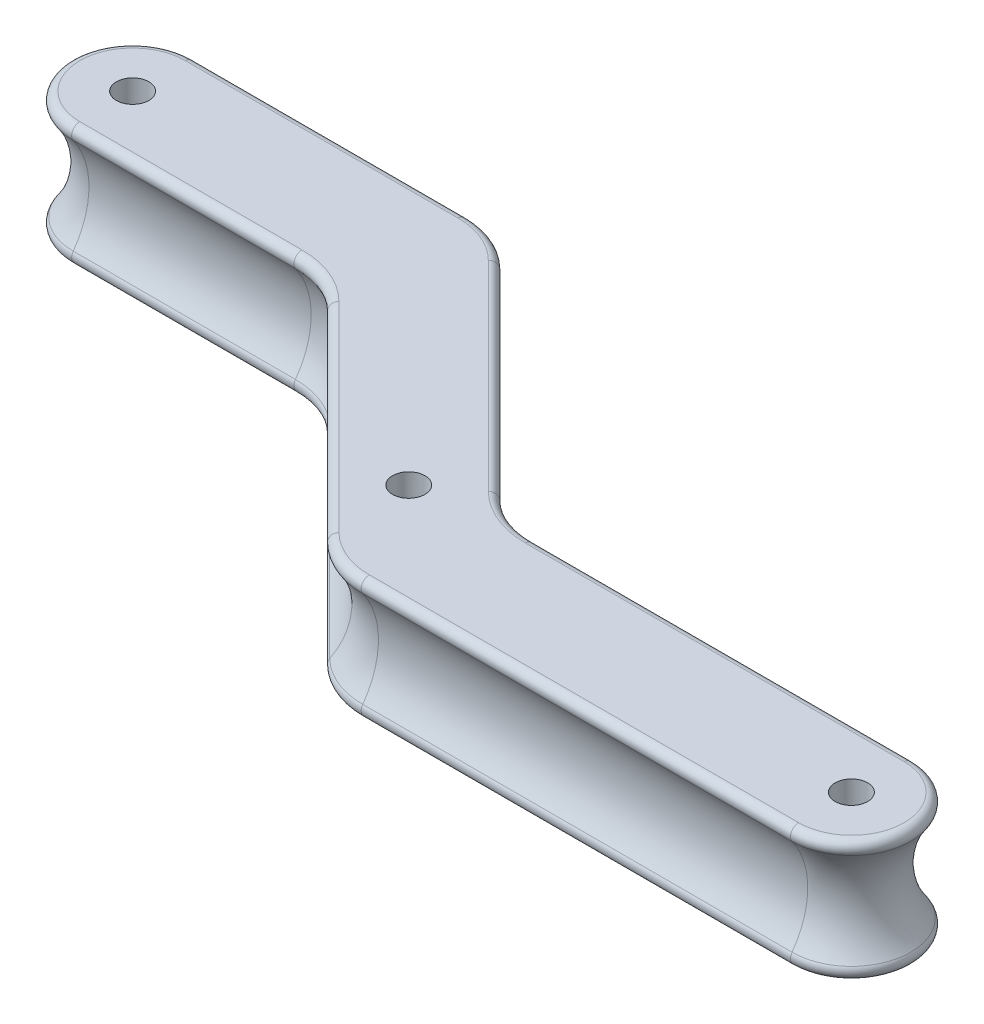
SolidWorks part; units mm, degrees
material "ABS"
ref_plane "前视基准面" through (0, 0, 0) normal (0, 0, 1) x (1, 0, 0)
ref_plane "上视基准面" through (0, 0, 0) normal (0, 1, 0) x (1, 0, 0)
ref_plane "右视基准面" through (0, 0, 0) normal (1, 0, 0) x (0, 0, -1)
sketch "草图1" plane through (0, 0, 0) normal (0, 1, 0) x (1, 0, 0)
  line L12 (-181.5, 30.5) -> (-150, 30.5)
  line L28 (-181.5, 45.5) -> (-143.7868, 45.5)
  line L31 (-150, 30.5) -> (-119.5, 0)
  line L39 (0, 0) -> (0, 70) construction
  line L61 (-113.2868, 15) -> (-62.5, 15)
  line L64 (-113.2868, 15) -> (-143.7868, 45.5)
  line L80 (-119.5, 0) -> (-62.5, 0)
  arc A9 (-181.5, 45.5) -> (-181.5, 30.5) centre (-181.5, 38) ccw
  arc A10 (-62.5, 0) -> (-62.5, 15) centre (-62.5, 7.5) ccw
  dimension "D3" = 119
  dimension "D5" = 15
  dimension "D6" = 15
  dimension "D9" = 45.5
  dimension "D8" = 150
  dimension "D2" = 62.5
  dimension "D18" = 135
  dimension "D19" = 15
extrude "凸台-拉伸1" add sketch "草图1" along normal mid plane 15
sketch "草图2" plane through (0, 7.5, 0) normal (0, 1, 0) x (1, 0, 0)
  line L0 (-143.7868, 45.5) -> (-181.5, 45.5) construction
  circle A0 centre (-62.5, 7.5) radius 2
  circle A41 centre (-181.5, 38) radius 2
  circle A42 centre (-122.5, 13) radius 2
  dimension "D2" = 32.5
  dimension "D3" = 59
  dimension "D19" = 4
extrude "切除-拉伸1" cut sketch "草图2" against normal through all
fillet "圆角1" radius 10 4 edges at (-150, 0, -30.5) (-143.7868, 0, -45.5) (-119.5, 0, 0) (-113.2868, 0, -15)
sketch "草图4" plane through (0, 7.5, 0) normal (0, 1, 0) x (1, 0, 0)
  line L16 (-62.5, 15) -> (-109.1447, 15)
  line L17 (-116.2157, 17.9289) -> (-140.8579, 42.5711)
  line L18 (-147.9289, 45.5) -> (-181.5, 45.5)
  line L23 (-181.5, 30.5) -> (-154.1421, 30.5)
  line L24 (-147.0711, 27.5711) -> (-122.4289, 2.9289)
  line L25 (-115.3579, 0) -> (-62.5, 0)
  line L29 (-62.5, 15) -> (-109.1447, 15)
  line L30 (-116.2157, 17.9289) -> (-140.8579, 42.5711)
  line L31 (-147.9289, 45.5) -> (-181.5, 45.5)
  line L36 (-181.5, 30.5) -> (-154.1421, 30.5)
  line L37 (-147.0711, 27.5711) -> (-122.4289, 2.9289)
  line L38 (-115.3579, 0) -> (-62.5, 0)
  arc A6 (-62.5, 0) -> (-62.5, 15) centre (-62.5, 7.5) ccw
  arc A7 (-62.5, 0) -> (-62.5, 15) centre (-62.5, 7.5) ccw
  arc A8 (-181.5, 45.5) -> (-181.5, 30.5) centre (-181.5, 38) ccw
  arc A9 (-181.5, 45.5) -> (-181.5, 30.5) centre (-181.5, 38) ccw
  arc A10 (-116.2157, 17.9289) -> (-109.1447, 15) centre (-109.1447, 25) ccw
  arc A11 (-116.2157, 17.9289) -> (-109.1447, 15) centre (-109.1447, 25) ccw
  arc A12 (-140.8579, 42.5711) -> (-147.9289, 45.5) centre (-147.9289, 35.5) ccw
  arc A13 (-140.8579, 42.5711) -> (-147.9289, 45.5) centre (-147.9289, 35.5) ccw
  arc A14 (-147.0711, 27.5711) -> (-154.1421, 30.5) centre (-154.1421, 20.5) ccw
  arc A15 (-147.0711, 27.5711) -> (-154.1421, 30.5) centre (-154.1421, 20.5) ccw
  arc A16 (-122.4289, 2.9289) -> (-115.3579, 0) centre (-115.3579, 10) ccw
  arc A17 (-122.4289, 2.9289) -> (-115.3579, 0) centre (-115.3579, 10) ccw
  dimension "D1" = 0
ref_plane "基准面1" through (-62.5, 0, 0) normal (1, 0, 0) x (0, 0, -1)
sketch "草图5" plane through (-62.5, 0, 0) normal (1, 0, 0) x (0, 0, -1)
  line L2 (15, 7.5) -> (0, 7.5) construction
  line L3 (0, 7.5) -> (0, -7.5) construction
  line L4 (1, 7.5) -> (-4, 7.5)
  line L5 (-4, 7.5) -> (-4, -7.5)
  line L6 (25.025, 0) -> (-25.025, 0) construction
  line L7 (1, -7.5) -> (-4, -7.5)
  arc A0 (1, 7.5) -> (0.1933, 5.9091) centre (1, 6.5) ccw
  arc A1 (0.1933, 5.9091) -> (0.1933, -5.9091) centre (-7.8741, 0) cw
  arc A2 (1, -7.5) -> (0.1933, -5.9091) centre (1, -6.5) cw
  dimension "D1" = 1
  dimension "D3" = 10
  dimension "D2" = 5
sweep "切除-扫描1" cut profiles "草图5" path "草图4"
